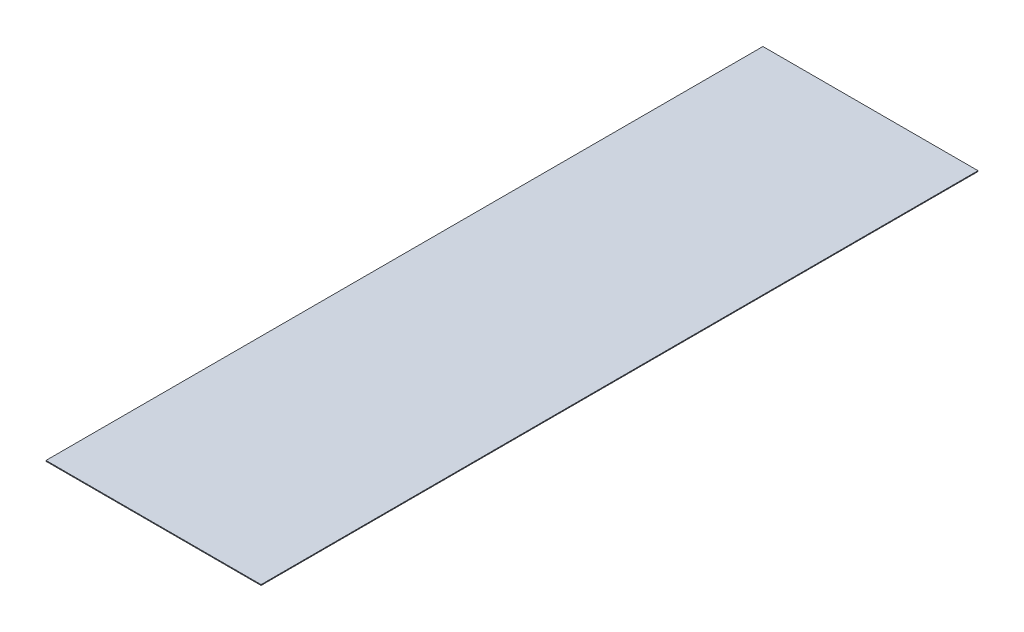
SolidWorks part; units mm, degrees
material "ASTM A36 Acero"
ref_plane "Alzado" through (0, 0, 0) normal (0, 0, 1) x (1, 0, 0)
ref_plane "Planta" through (0, 0, 0) normal (0, 1, 0) x (1, 0, 0)
ref_plane "Vista lateral" through (0, 0, 0) normal (1, 0, 0) x (0, 0, -1)
sketch "Croquis1" plane through (0, 0, 0) normal (0, 1, 0) x (1, 0, 0)
  line L1 (-457.2, -1524) -> (457.2, -1524)
  line L2 (-457.2, -1524) -> (-457.2, 1524)
  line L3 (-457.2, 1524) -> (457.2, 1524)
  line L4 (457.2, -1524) -> (457.2, 1524)
  line L5 (-457.2, -1524) -> (457.2, 1524) construction
  line L6 (-457.2, 1524) -> (457.2, -1524) construction
  point P0 (0, 0)
  dimension "D1" = 3048
  dimension "D2" = 914.4
extrude "Saliente-Extruir1" add sketch "Croquis1" along normal blind 3.4
